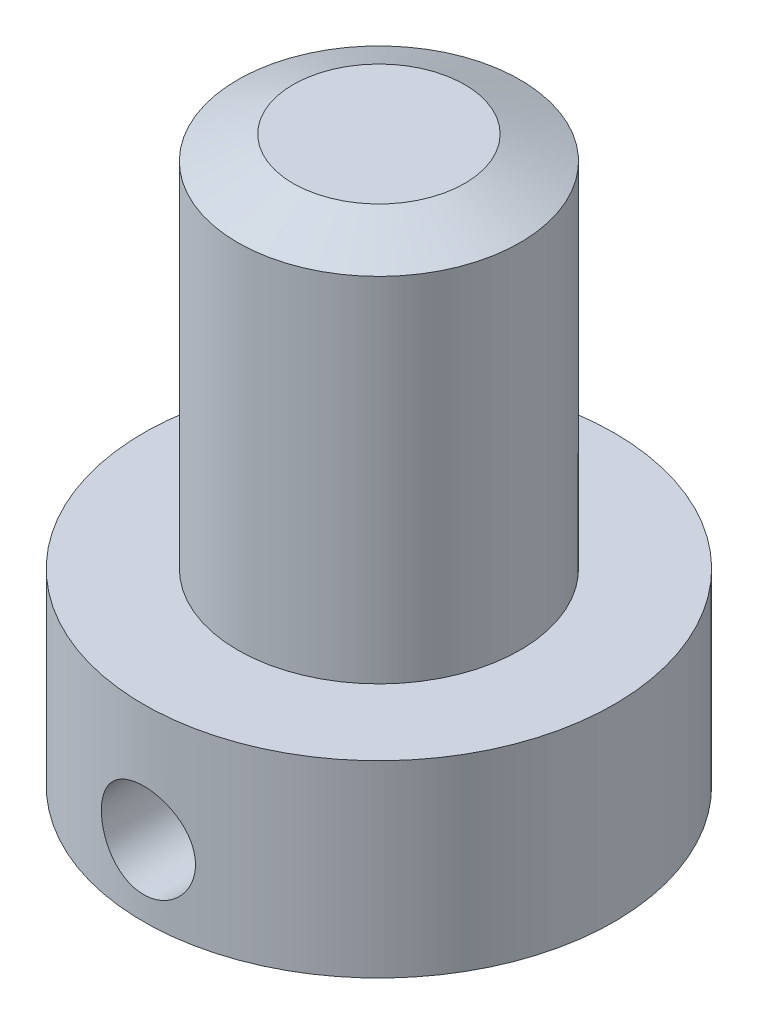
SolidWorks part; units mm, degrees
ref_plane "Front Plane" through (0, 0, 0) normal (0, 0, 1) x (1, 0, 0)
ref_plane "Top Plane" through (0, 0, 0) normal (0, 1, 0) x (1, 0, 0)
ref_plane "Right Plane" through (0, 0, 0) normal (1, 0, 0) x (0, 0, -1)
sketch "Sketch1" plane through (0, 0, 0) normal (0, 1, 0) x (1, 0, 0)
  circle A0 centre (0, 0) radius 3
  dimension "D1" = 6
extrude "Boss-Extrude1" add sketch "Sketch1" along normal blind 8
sketch "Sketch2" plane through (0, 0, 0) normal (0, -1, 0) x (1, 0, 0)
  circle A0 centre (0, 0) radius 5
  dimension "D1" = 10
extrude "Boss-Extrude2" add sketch "Sketch2" along normal blind 5
sketch "Sketch3" plane through (0, 0, 0) normal (0, 0, 1) x (1, 0, 0)
  circle A0 centre (0, -2.5) radius 1
  dimension "D1" = 2
  dimension "D2" = 2.5
extrude "Cut-Extrude1" cut sketch "Sketch3" against normal through all both and the other way through all
chamfer "Chamfer1" distance 1 angle 67 1 edges at (0, -5, -5)
chamfer "Chamfer2" distance 0.5 angle 67 1 edges at (0, 8, 3)
